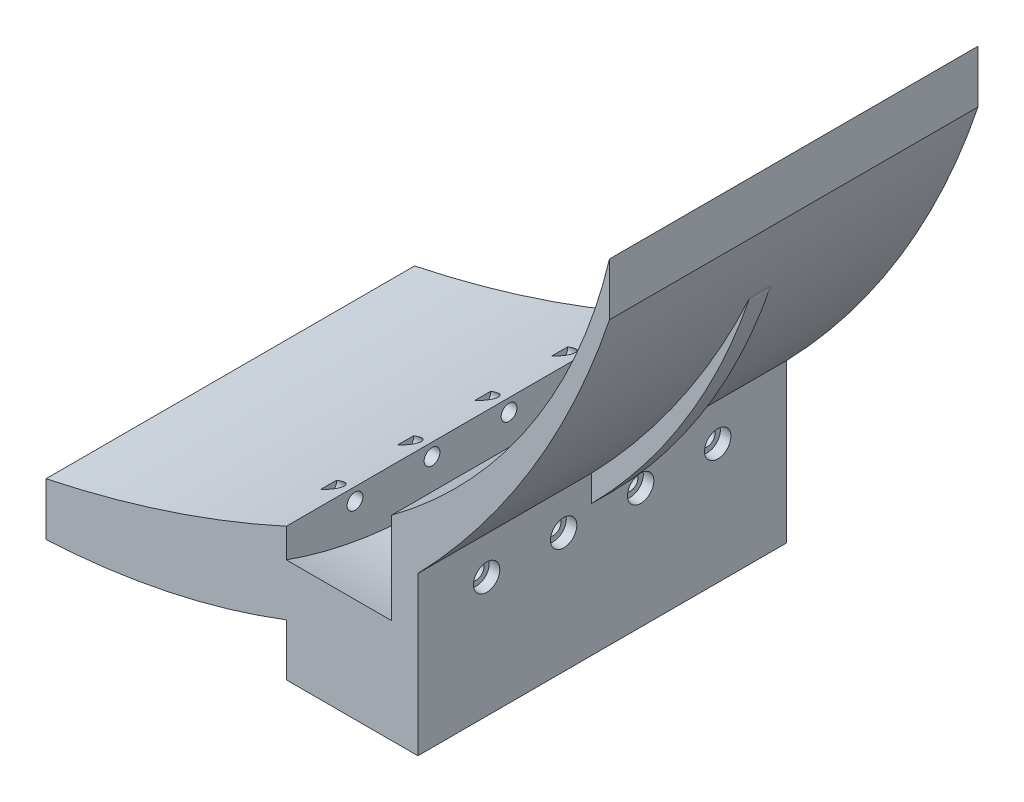
SolidWorks part; units mm, degrees
ref_plane "前视基准面" through (0, 0, 0) normal (0, 0, 1) x (1, 0, 0)
ref_plane "上视基准面" through (0, 0, 0) normal (0, 1, 0) x (1, 0, 0)
ref_plane "右视基准面" through (0, 0, 0) normal (1, 0, 0) x (0, 0, -1)
sketch "草图1" plane through (0, 0, 0) normal (0, 0, 1) x (1, 0, 0)
  line L1 (-12.5, -15) -> (12.5, -15)
  line L2 (-12.5, -15) -> (-12.5, 15)
  line L3 (-12.5, 15) -> (12.5, 15)
  line L4 (12.5, -15) -> (12.5, 15)
  line L5 (-12.5, -15) -> (12.5, 15) construction
  line L6 (-12.5, 15) -> (12.5, -15) construction
  point P0 (0, 0)
  dimension "D1" = 25
  dimension "D2" = 30
extrude "凸台-拉伸1" add sketch "草图1" along normal blind 70
sketch "草图2" plane through (0, 0, 0) normal (1, 0, 0) x (0, 0, -1)
  line L2 (-42.9, 0) -> (-27.1, 0)
  line L4 (19.5369, 15) -> (-89.5369, 15)
  line L6 (-35, -1015) -> (-35, 48985) construction
  line L7 (-70, -15) -> (0, -15) construction
  line L8 (-70, 15) -> (0, 15) construction
  line L9 (-27.1, 0) -> (0, 0) construction
  arc A0 (-42.9, 0) -> (-89.5369, 15) centre (-42.9, 80) cw
  arc A1 (-27.1, 0) -> (19.5369, 15) centre (-27.1, 80) ccw
  point P3 (45.8487, 15)
  point P8 (-65.7927, 15)
  point P14 (-35, -15)
  point P17 (-35, 15)
  dimension "D1" = 80
  dimension "D2" = 15.8
extrude "切除-拉伸1" cut sketch "草图2" against normal blind 20 and the other way blind 7.5
ref_plane "基准面4" through (0, 0, 35) normal (0, 0, 1) x (1, 0, 0)
sketch "草图3" plane through (0, 0, 35) normal (0, 0, 1) x (1, 0, 0)
  line L0 (7.5, 0) -> (-58.1371, 0) construction
  line L1 (-58.1371, 0) -> (-58.1371, 110.3465) construction
  point P5 (-60.6371, 109.7351)
  point P6 (-60.64, 0)
  point P7 (-60.6371, 110.3465)
  point P9 (-60.6371, 110.3465)
sketch "草图4" plane through (0, 0, 35) normal (0, 0, 1) x (1, 0, 0)
  line L0 (12.5, -15) -> (12.5, 15) construction
  line L1 (48.8834, 84.9177) -> (48.8834, 74.9177)
  line L2 (7.5, 15) -> (12.5, 15)
  line L3 (7.5, 15) -> (7.5, 22.0755)
  line L4 (-58.1371, 110.3465) -> (48.8834, 84.9177) construction
  line L5 (-58.1371, 110.3465) -> (7.5, 22.0755) construction
  arc A2 (7.5, 22.0755) -> (48.8834, 84.9177) centre (-58.1371, 110.3465) ccw
  arc A5 (12.5, 15) -> (48.8834, 74.9177) centre (-100.7256, 124.7583) ccw
  point P2 (0, 0)
  point P13 (0, 0)
  point P16 (5, 16.865)
  dimension "D1" = 10
  dimension "D2" = 40
extrude "凸台-拉伸2" add sketch "草图4" along normal up to surface and the other way up to surface contours L2 A5 L1 A2 L3 up to face at (2.5, 1.5766, 70) other way up to face at (2.5, 1.5766, 0)
sketch "草图5" plane through (0, 0, 35) normal (0, 0, 1) x (1, 0, 0)
  line L0 (12.5, -15) -> (12.5, 15) construction
  line L1 (12.5, 15) -> (12.5, 10)
  arc A0 (42.5, 58.7783) -> (12.5, 15) centre (-100.7256, 124.7583) cw
  arc A1 (12.5, 15) -> (48.8834, 74.9177) centre (-100.7256, 124.7583) ccw construction
  arc A2 (42.5, 58.7783) -> (12.5, 10) centre (-77.614, 99.0371) cw
  dimension "D1" = 5
  dimension "D2" = 30
extrude "凸台-拉伸3" add sketch "草图5" along normal blind 2 and the other way blind 2
sketch "草图6" plane through (0, 0, 35) normal (0, 0, 1) x (1, 0, 0)
  line L0 (-58.1371, -889.6535) -> (-58.1371, 49110.3465) construction
  line L3 (-58.1371, -4.7397) -> (-58.1371, -14.7397)
  line L4 (-12.5, 10.2603) -> (-58.1371, 10.2603) construction
  line L5 (-12.5, 4.7299) -> (-12.5, -15) construction
  line L6 (-12.5, -5.1351) -> (-12.5, 10.2603)
  arc A0 (-12.5, 10.2603) -> (-58.1371, -4.7397) centre (-103.0656, 208.8789) cw
  arc A1 (-12.5, -5.1351) -> (-58.1371, -14.7397) centre (-65.4345, 133.1597) cw
  arc A2 (-12.5, 10.2603) -> (7.5, 22.0755) centre (-58.1371, 110.3465) ccw construction
  point P30 (-12.5, -5.1351)
  dimension "D1" = 15
  dimension "D2" = 10
extrude "凸台-拉伸4" add sketch "草图6" along normal up to surface and the other way up to surface contours A1 L3 A0 L6 up to face at (15.2098, 21.3344, 70) other way up to face at (15.2098, 21.3344, 0)
sketch "草图7" plane through (12.5, 0, 0) normal (1, 0, 0) x (0, 0, -1)
  line L0 (-13.0539, 7.857) -> (-27.6846, 7.857) construction
  line L1 (-35, -915.0823) -> (-35, 49084.9177) construction
  line L2 (-70, 84.9177) -> (0, 84.9177) construction
  line L3 (-27.6846, 7.857) -> (-42.3154, 7.857) construction
  line L4 (-42.3154, 7.857) -> (-56.9461, 7.857) construction
  circle A0 centre (-27.6846, 7.857) radius 1.5
  circle A1 centre (-42.3154, 7.857) radius 1.5
  circle A2 centre (-56.9461, 7.857) radius 1.5
  circle A3 centre (-13.0539, 7.857) radius 1.5
  point P0 (-35, 7.857)
  point P2 (-13.0539, 7.857)
  point P8 (-35, 84.9177)
  dimension "D1" = 3
extrude "切除-拉伸2" cut sketch "草图7" against normal blind 30
sketch "草图8" plane through (12.5, 0, 0) normal (1, 0, 0) x (0, 0, -1)
  circle A0 centre (-56.9461, 7.857) radius 2.5
  circle A1 centre (-42.3154, 7.857) radius 2.5
  circle A2 centre (-27.6846, 7.857) radius 2.5
  circle A3 centre (-13.0539, 7.857) radius 2.5
  dimension "D1" = 5
  dimension "D2" = 5
  dimension "D3" = 5
  dimension "D4" = 5
extrude "切除-拉伸3" cut sketch "草图8" against normal blind 2
